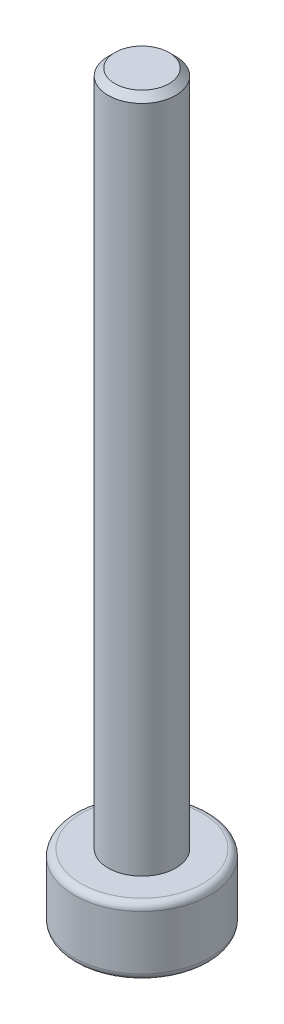
SolidWorks part; units mm, degrees
material "AISI 304"
ref_plane "前视基准面" through (0, 0, 0) normal (0, 0, 1) x (1, 0, 0)
ref_plane "上视基准面" through (0, 0, 0) normal (0, 1, 0) x (1, 0, 0)
ref_plane "右视基准面" through (0, 0, 0) normal (1, 0, 0) x (0, 0, -1)
sketch "草图2" plane through (0, 0, 0) normal (0, 1, 0) x (1, 0, 0)
  circle A0 centre (0, 0) radius 2
  dimension "D1" = 4
extrude "凸台-拉伸1" add sketch "草图2" along normal blind 2
sketch "草图3" plane through (0, 2, 0) normal (0, 1, 0) x (1, 0, 0)
  circle A0 centre (0, 0) radius 1
  dimension "D1" = 2
extrude "凸台-拉伸2" add sketch "草图3" along normal blind 20
fillet "圆角1" radius 0.2 2 edges at (0, 2, 2) (0, 0, 2)
sketch "草图4" plane through (0, 0, 0) normal (0, -1, 0) x (1, 0, 0)
  circle A0 centre (0, 0) radius 0.765
  dimension "D1" = 1.53
extrude "切除-拉伸1" cut sketch "草图4" against normal blind 1.52
chamfer "倒角1" distance 0.1 angle 45 1 edges at (0, 0, -0.765)
chamfer "倒角2" distance 0.2 angle 45 1 edges at (0, 22, 1)
